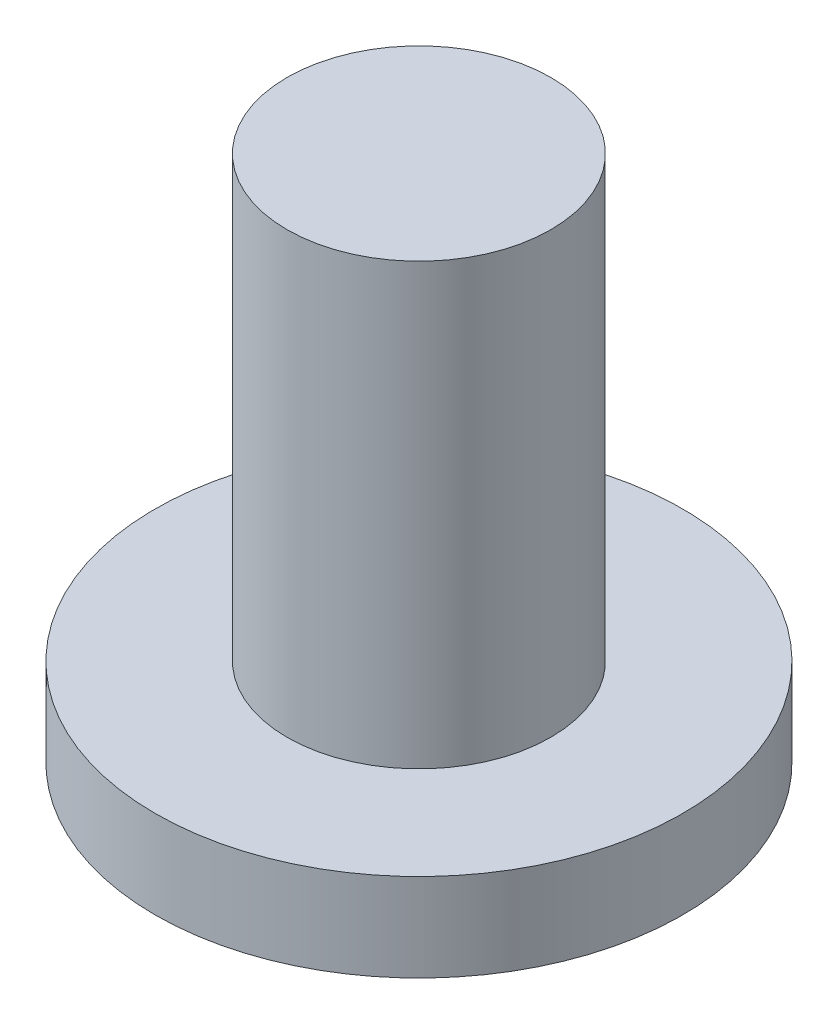
SolidWorks part; units mm, degrees
ref_plane "前视基准面" through (0, 0, 0) normal (0, 0, 1) x (1, 0, 0)
ref_plane "上视基准面" through (0, 0, 0) normal (0, 1, 0) x (1, 0, 0)
ref_plane "右视基准面" through (0, 0, 0) normal (1, 0, 0) x (0, 0, -1)
other "Configuration Table"
sketch "草图1" plane through (0, 0, 0) normal (0, 1, 0) x (1, 0, 0)
  circle A0 centre (0, 0) radius 6
  dimension "D1" = 12
extrude "凸台-拉伸1" add sketch "草图1" along normal blind 2
sketch "草图2" plane through (0, 0, 0) normal (0, 1, 0) x (1, 0, 0)
  circle A0 centre (0, 0) radius 3
  dimension "D1" = 6
extrude "凸台-拉伸2" add sketch "草图2" along normal blind 10 from surface at 2 starting at face at (0, 2, 6)
